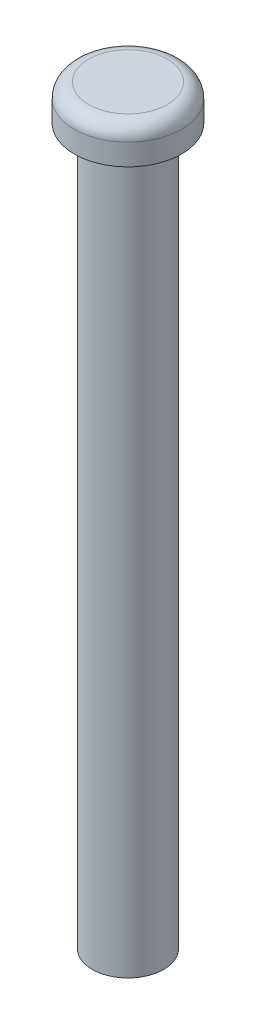
SolidWorks part; units mm, degrees
ref_plane "Front Plane" through (0, 0, 0) normal (0, 0, 1) x (1, 0, 0)
ref_plane "Top Plane" through (0, 0, 0) normal (0, 1, 0) x (1, 0, 0)
ref_plane "Right Plane" through (0, 0, 0) normal (1, 0, 0) x (0, 0, -1)
sketch "Sketch1" plane through (0, 0, 0) normal (0, 1, 0) x (1, 0, 0)
  circle A0 centre (0, 0) radius 5
  dimension "D1" = 10
extrude "Boss-Extrude1" add sketch "Sketch1" along normal blind 100
sketch "Sketch2" plane through (0, 100, 0) normal (0, 1, 0) x (1, 0, 0)
  circle A0 centre (0, 0) radius 7.5
  dimension "D1" = 15
extrude "Boss-Extrude2" add sketch "Sketch2" along normal blind 5
fillet "Fillet1" radius 2 1 edges at (0, 105, 7.5)
